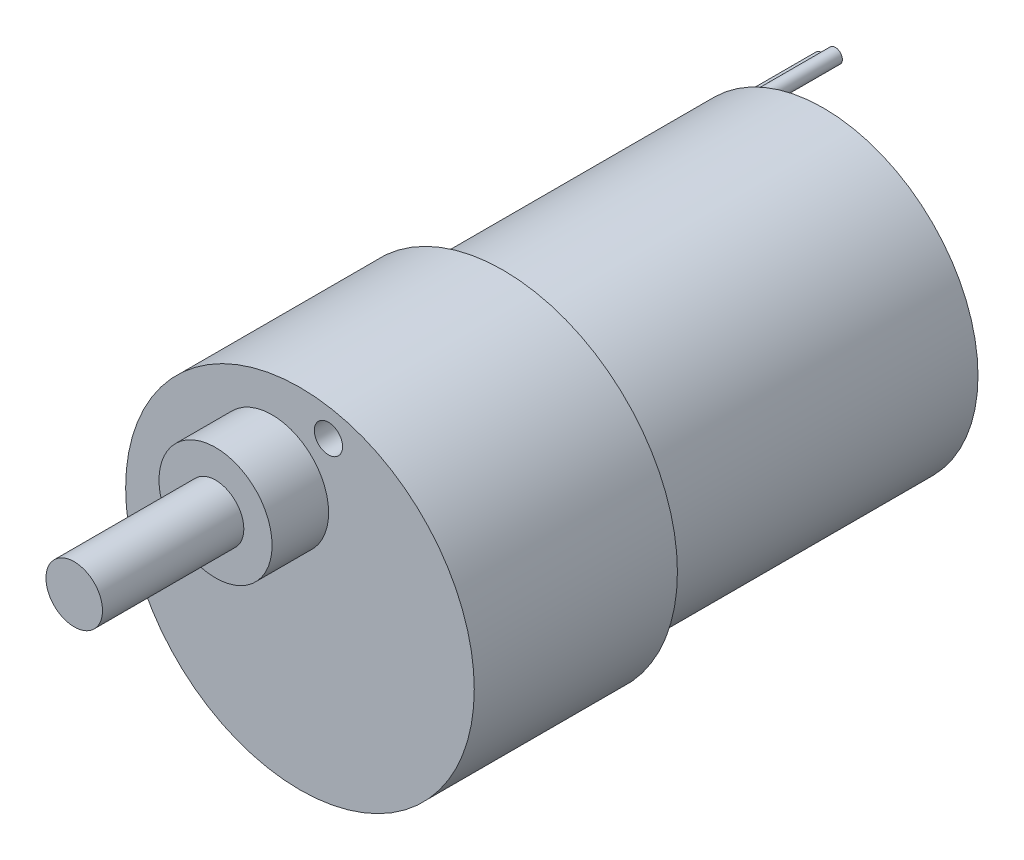
SolidWorks part; units mm, degrees
ref_plane "Front Plane" through (0, 0, 0) normal (0, 0, 1) x (1, 0, 0)
ref_plane "Top Plane" through (0, 0, 0) normal (0, 1, 0) x (1, 0, 0)
ref_plane "Right Plane" through (0, 0, 0) normal (1, 0, 0) x (0, 0, -1)
sketch "Sketch1" plane through (0, 0, 0) normal (0, 0, 1) x (1, 0, 0)
  circle A0 centre (-38.6606, 1.9397) radius 18.5
  dimension "D1" = 37
extrude "Boss-Extrude1" add sketch "Sketch1" along normal blind 21.56
sketch "Sketch2" plane through (0, 0, 21.56) normal (0, 0, 1) x (1, 0, 0)
  circle A0 centre (-41.6189, 10.4397) radius 6
  circle A1 centre (-38.6606, 1.9397) radius 18.5 construction
  dimension "D1" = 12
  dimension "D2" = 9
extrude "Boss-Extrude2" add sketch "Sketch2" along normal blind 6
sketch "Sketch3" plane through (0, 0, 27.56) normal (0, 0, 1) x (1, 0, 0)
  circle A0 centre (-41.6189, 10.4397) radius 3
  circle A1 centre (-41.6189, 10.4397) radius 6 construction
  dimension "D1" = 6
  dimension "D2" = 0
extrude "Boss-Extrude3" add sketch "Sketch3" along normal blind 15
sketch "Sketch4" plane through (0, 0, 21.56) normal (0, 0, 1) x (1, 0, 0)
  circle A0 centre (-35.6386, 17.2482) radius 1.5
  point P2 (-35.7895, 18.0387)
  point P3 (0, 0)
  point P4 (-35.6386, 17.2482)
  dimension "D1" = 3
extrude "Cut-Extrude1" cut sketch "Sketch4" against normal blind 4
sketch "Sketch5" plane through (0, 0, 0) normal (0, 0, -1) x (-1, 0, 0)
  circle A0 centre (38.6606, 1.9397) radius 16.4
  circle A1 centre (38.6606, 1.9397) radius 18.5 construction
  dimension "D1" = 0
  dimension "D2" = 32.8
extrude "Boss-Extrude4" add sketch "Sketch5" along normal blind 34
sketch "Sketch7" plane through (0, 0, -34) normal (0, 0, -1) x (-1, 0, 0)
  circle A0 centre (47.4067, 13.7941) radius 0.75
  dimension "D1" = 1.5
extrude "Boss-Extrude5" add sketch "Sketch7" along normal blind 10
sketch "Sketch8" plane through (0, 0, -34) normal (0, 0, -1) x (-1, 0, 0)
  circle A0 centre (48.9022, 12.5824) radius 0.75
  dimension "D1" = 1.5
extrude "Boss-Extrude6" add sketch "Sketch8" along normal blind 10
